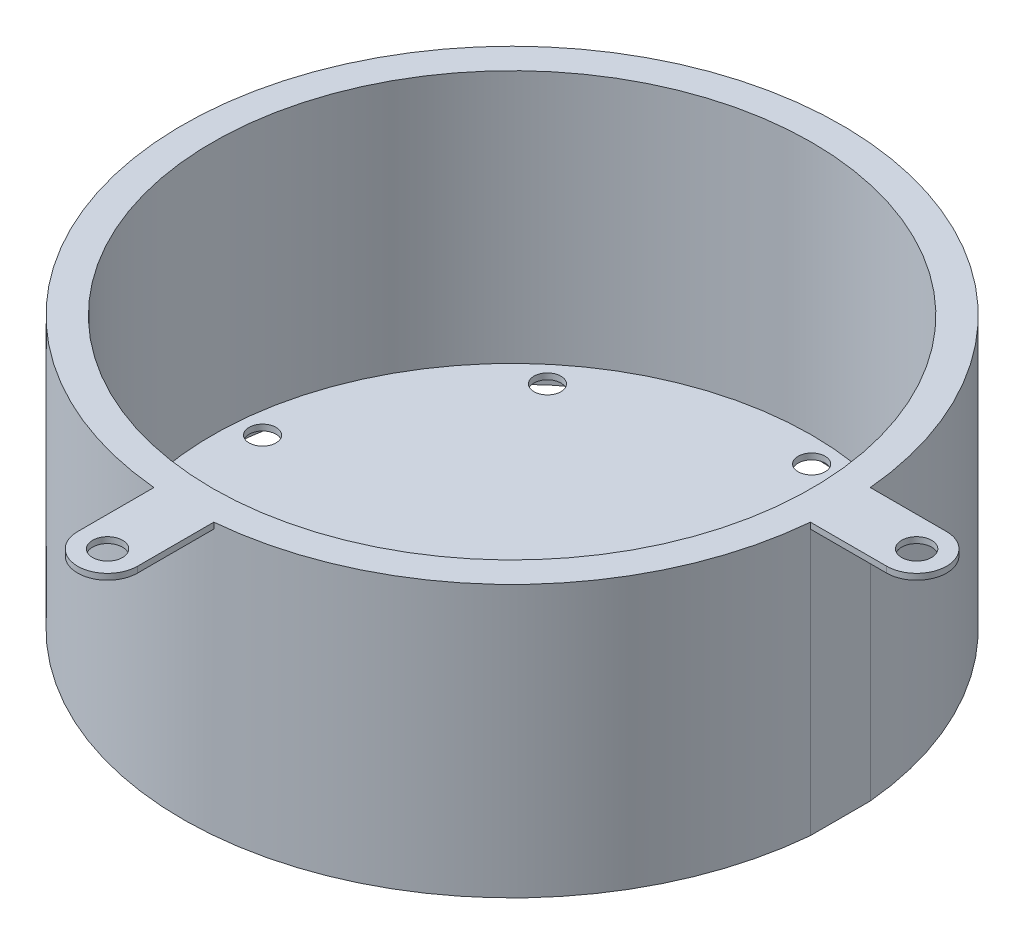
SolidWorks part; units mm, degrees
ref_plane "前视基准面" through (0, 0, 0) normal (0, 0, 1) x (1, 0, 0)
ref_plane "上视基准面" through (0, 0, 0) normal (0, 1, 0) x (1, 0, 0)
ref_plane "右视基准面" through (0, 0, 0) normal (1, 0, 0) x (0, 0, -1)
sketch "草图1" plane through (0, 0, 0) normal (0, 1, 0) x (1, 0, 0)
  line L2 (54.7723, 5) -> (67.5, 5)
  line L3 (54.7723, -5) -> (67.5, -5)
  arc A0 (54.7723, 5) -> (54.7723, -5) centre (0, 0) ccw
  arc A2 (67.5, -5) -> (67.5, 5) centre (67.5, 0) ccw
  point P7 (55, 0)
extrude "凸台-拉伸1" add sketch "草图1" along normal blind 45.3
sketch "草图2" plane through (0, 45.3, 0) normal (0, 1, 0) x (1, 0, 0)
  circle A0 centre (0, 0) radius 50
extrude "切除-拉伸1" cut sketch "草图2" against normal blind 42.3
sketch "草图4" plane through (0, 0, 0) normal (0, -1, 0) x (1, 0, 0)
  line L0 (54.7723, 5) -> (67.5, 5)
  line L1 (67.5, 5) -> (67.5, -5)
  line L2 (67.5, -5) -> (54.7723, -5)
  line L3 (54.7723, -5) -> (54.7723, 5)
  circle A0 centre (67.5, 0) radius 5
  line M2 (54.7723, -5) -> (67.5, -5)
  arc M3 (67.5, -5) -> (67.5, 5) centre (67.5, 0) ccw
  line M4 (67.5, 5) -> (54.7723, 5)
extrude "切除-拉伸3" cut sketch "草图4" against normal blind 44.3 contours L1 M3 | L1 A0 | A0 L3 M4 M2
sketch "草图5" plane through (0, 0, 0) normal (0, -1, 0) x (1, 0, 0)
  circle A0 centre (0, 0) radius 50
extrude "切除-拉伸4" cut sketch "草图5" against normal blind 2
sketch "草图6" plane through (0, 2, 0) normal (0, -1, 0) x (-1, 0, 0)
  circle A1 centre (-4.1709, 45.8105) radius 2.25
  circle A2 centre (29.4436, 35.3422) radius 2.25
  circle A3 centre (45.8105, 4.1709) radius 2.25
  circle A4 centre (35.3422, -29.4436) radius 2.25
  circle A5 centre (4.1709, -45.8105) radius 2.25
  circle A6 centre (-29.4436, -35.3422) radius 2.25
  circle A7 centre (-45.8105, -4.1709) radius 2.25
  circle A8 centre (-35.3422, 29.4436) radius 2.25
  point P21 (0, 0)
  dimension "D1" = 8
extrude "切除-拉伸5" cut sketch "草图6" against normal through all
sketch "草图7" plane through (0, 2, 0) normal (0, -1, 0) x (1, 0, 0)
  circle A0 centre (0, 0) radius 2.5
extrude "切除-拉伸6" cut sketch "草图7" against normal through all
sketch "草图8" plane through (0, 44.3, 0) normal (0, -1, 0) x (1, 0, 0)
  circle A0 centre (67.5, 0) radius 2.5
extrude "切除-拉伸7" cut sketch "草图8" against normal through all
sketch "草图9" plane through (0, 45.3, 0) normal (0, 1, 0) x (1, 0, 0)
  line L0 (0, -42.5) -> (0, -67.5) construction
  line L1 (5, -42.5) -> (5, -67.5)
  line L2 (-5, -42.5) -> (-5, -67.5)
  line L3 (5, -54.7187) -> (0, -55)
  line L4 (0, -55) -> (-5, -54.7187)
  arc A0 (54.7723, 5) -> (54.7723, -5) centre (0, 0) ccw construction
  arc A1 (5, -42.5) -> (-5, -42.5) centre (0, -42.5) ccw
  arc A2 (-5, -67.5) -> (5, -67.5) centre (0, -67.5) ccw
  point P7 (0, -55)
extrude "凸台-拉伸2" add sketch "草图9" against normal blind 1
sketch "草图10" plane through (0, 45.3, 0) normal (0, 1, 0) x (1, 0, 0)
  circle A0 centre (0, -67.5) radius 2.5
extrude "切除-拉伸8" cut sketch "草图10" against normal blind 1
